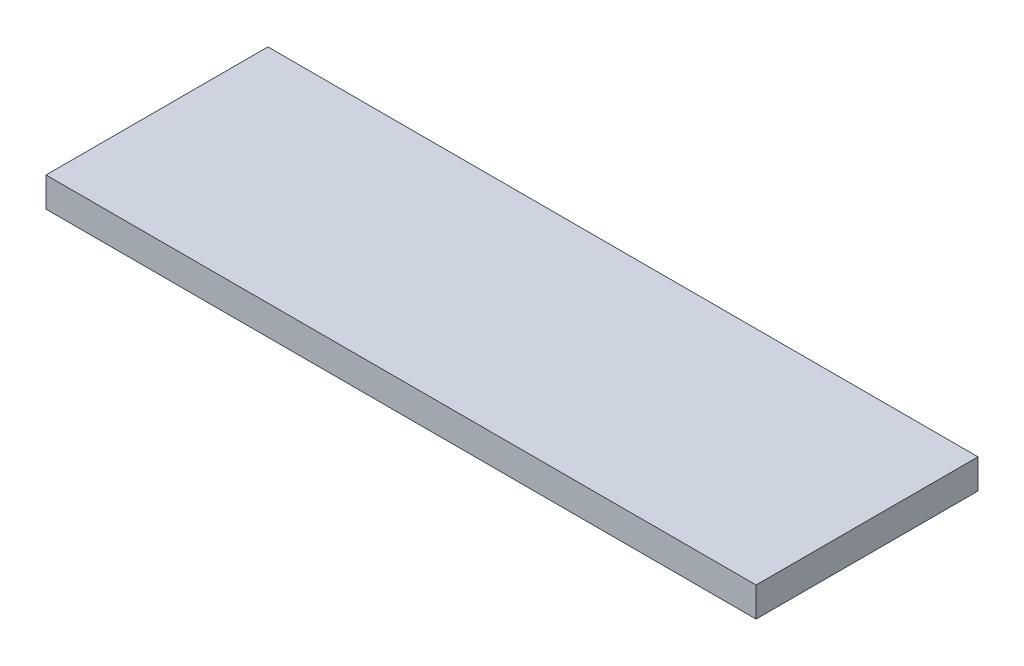
SolidWorks part; units mm, degrees
ref_plane "Front Plane" through (0, 0, 0) normal (0, 0, 1) x (1, 0, 0)
ref_plane "Top Plane" through (0, 0, 0) normal (0, 1, 0) x (1, 0, 0)
ref_plane "Right Plane" through (0, 0, 0) normal (1, 0, 0) x (0, 0, -1)
sketch "Sketch1" plane through (0, 0, 0) normal (0, 1, 0) x (1, 0, 0)
  line L1 (0, 0) -> (96, 0)
  line L2 (0, 0) -> (0, -30)
  line L3 (0, -30) -> (96, -30)
  line L4 (96, 0) -> (96, -30)
  dimension "D1" = 96
  dimension "D2" = 30
extrude "Boss-Extrude1" add sketch "Sketch1" along normal blind 4
